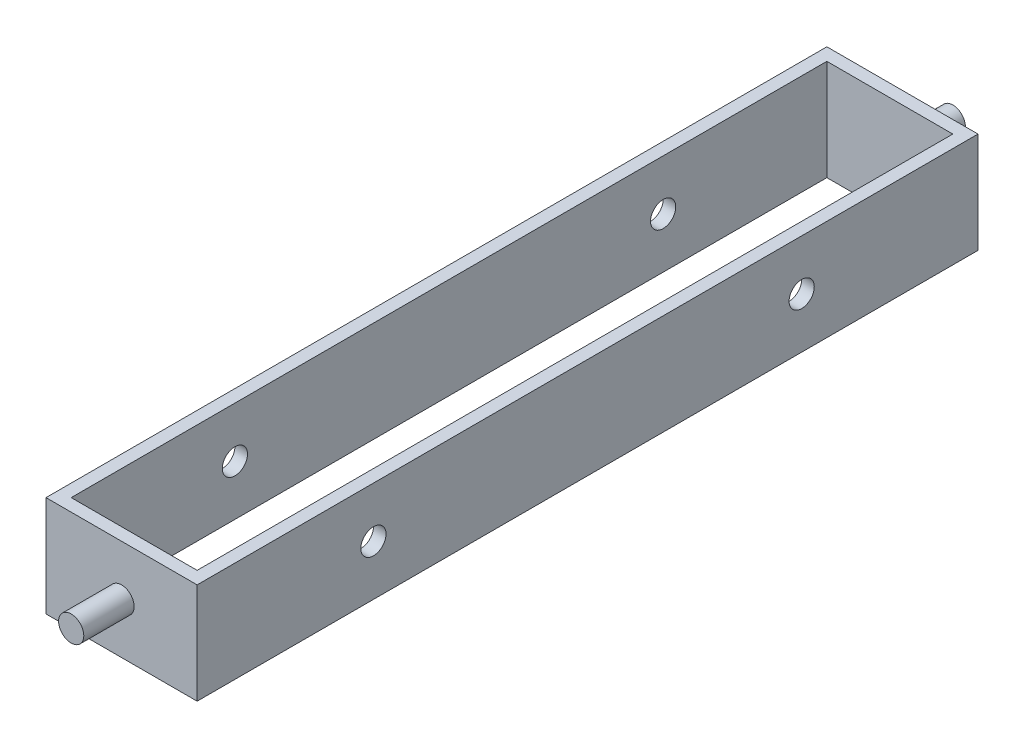
SolidWorks part; units mm, degrees
ref_plane "Спереди" through (0, 0, 0) normal (0, 0, 1) x (1, 0, 0)
ref_plane "Сверху" through (0, 0, 0) normal (0, 1, 0) x (1, 0, 0)
ref_plane "Справа" through (0, 0, 0) normal (1, 0, 0) x (0, 0, -1)
sketch "Эскиз7" plane through (0, 0, 0) normal (0, 0, 1) x (1, 0, 0)
  circle A0 centre (0, 0) radius 5
  dimension "D1" = 10
extrude "Бобышка-Вытянуть5" add sketch "Эскиз7" along normal blind 20
sketch "Эскиз8" plane through (0, 0, 20) normal (0, 0, 1) x (1, 0, 0)
  line L1 (-30, -20) -> (30, -20)
  line L2 (-30, -20) -> (-30, 20)
  line L3 (-30, 20) -> (30, 20)
  line L4 (30, -20) -> (30, 20)
  line L5 (-30, -20) -> (30, 20) construction
  line L6 (-30, 20) -> (30, -20) construction
  point P0 (0, 0)
  dimension "D1" = 40
  dimension "D2" = 60
extrude "Бобышка-Вытянуть7" add sketch "Эскиз8" along normal blind 5
sketch "Эскиз9" plane through (0, 0, 25) normal (0, 0, 1) x (1, 0, 0)
  line L0 (30, -20) -> (30, 20) construction
  line L1 (30, 20) -> (-30, 20) construction
  line L2 (-30, 20) -> (-30, -20) construction
  line L3 (-30, -20) -> (30, -20) construction
  line L4 (30, -20) -> (30, 20)
  line L5 (30, 20) -> (-30, 20)
  line L6 (-30, 20) -> (-30, -20)
  line L7 (-30, -20) -> (30, -20)
  line L8 (25, 20) -> (25, -20)
  line L13 (-25, 20) -> (-25, -20)
  line M8 (30, -20) -> (30, 20)
  line M9 (30, 20) -> (-30, 20)
  line M10 (-30, 20) -> (-30, -20)
  line M11 (-30, -20) -> (30, -20)
  dimension "D1" = 5
  dimension "D2" = 5
extrude "Бобышка-Вытянуть8" add sketch "Эскиз9" along normal blind 300 contours L13 M9 M10 M11 | L8 L7 M9 M8
sketch "Эскиз10" plane through (0, 0, 325) normal (0, 0, 1) x (1, 0, 0)
  line L1 (-30, 20) -> (30, 20)
  line L2 (-30, 20) -> (-30, -20)
  line L3 (-30, -20) -> (30, -20)
  line L4 (30, 20) -> (30, -20)
extrude "Бобышка-Вытянуть9" add sketch "Эскиз10" along normal blind 5
sketch "Эскиз11" plane through (0, 0, 330) normal (0, 0, 1) x (1, 0, 0)
  circle A0 centre (0, 0) radius 5
  dimension "D1" = 10
extrude "Бобышка-Вытянуть10" add sketch "Эскиз11" along normal blind 20 contours A0
sketch "Эскиз12" plane through (30, 0, 0) normal (1, 0, 0) x (0, 0, -1)
  line L0 (-330, 0) -> (-20, 0) construction
  line L1 (-330, 5) -> (-330, -5) construction
  line L2 (-20, -20) -> (-20, 20) construction
  line L3 (-175, 20) -> (-175, -20) construction
  line L4 (-330, 20) -> (-20, 20) construction
  line L5 (-330, -20) -> (-20, -20) construction
  circle A0 centre (-90, 0) radius 5
  circle A1 centre (-260, 0) radius 5
  dimension "D1" = 10
  dimension "D2" = 70
extrude "Вырез-Вытянуть1" cut sketch "Эскиз12" against normal blind 96
